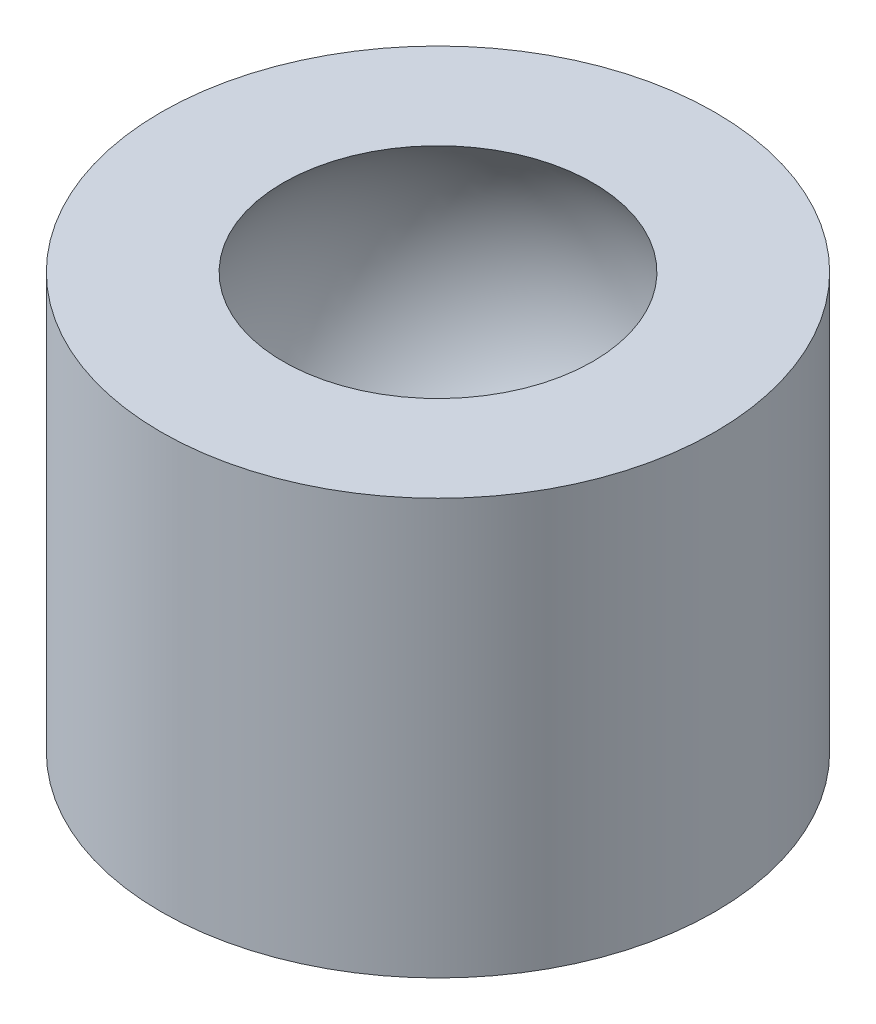
SolidWorks part; units mm, degrees
ref_plane "Płaszczyzna przednia" through (0, 0, 0) normal (0, 0, 1) x (1, 0, 0)
ref_plane "Płaszczyzna górna" through (0, 0, 0) normal (0, 1, 0) x (1, 0, 0)
ref_plane "Płaszczyzna prawa" through (0, 0, 0) normal (1, 0, 0) x (0, 0, -1)
sketch "Szkic1" plane through (0, 0, 0) normal (0, 0, 1) x (1, 0, 0)
  line L1 (0, 0) -> (-20, 0)
  line L2 (0, 0) -> (0, 30)
  line L3 (0, 30) -> (-20, 30)
  line L4 (-20, 0) -> (-20, 30)
  circle A2 centre (0, 20) radius 15
  dimension "D1" = 30
  dimension "D3" = 10
  dimension "D4" = 30
  dimension "D2" = 20
revolve "Obrót1" add sketch "Szkic1" angle 360 about L2
